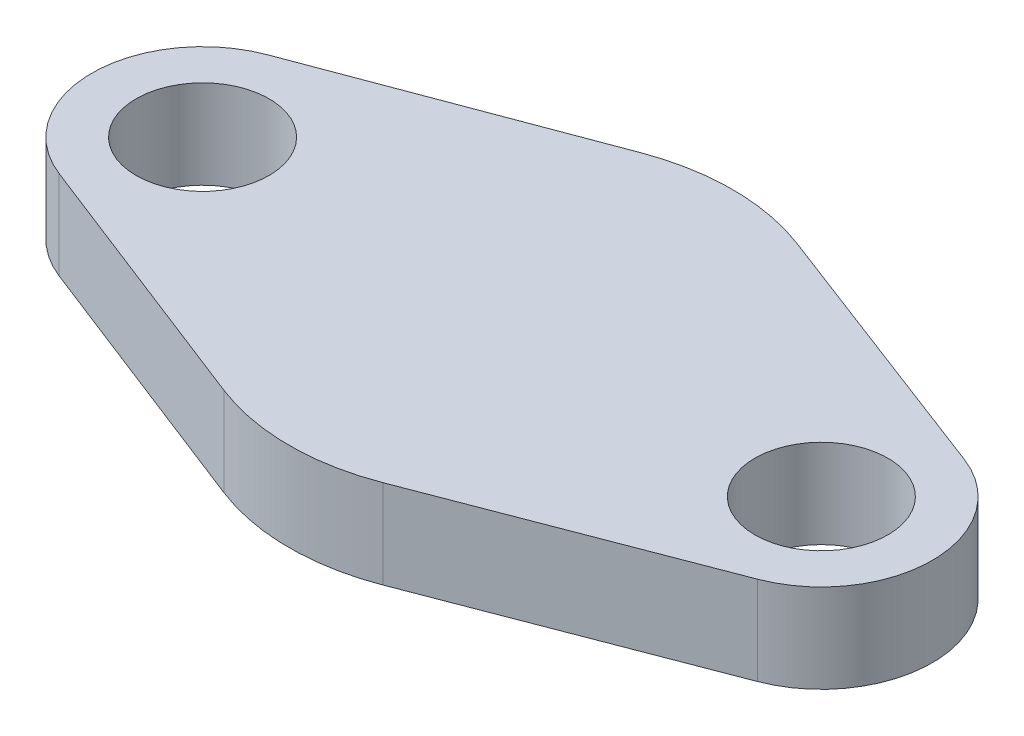
SolidWorks part; units mm, degrees
ref_plane "Plane1" through (0, 0, 0) normal (0, 0, 1) x (1, 0, 0)
ref_plane "Plane2" through (0, 0, 0) normal (0, 1, 0) x (1, 0, 0)
ref_plane "Plane3" through (0, 0, 0) normal (1, 0, 0) x (0, 0, -1)
sketch "Эскиз1" plane through (0, 0, 0) normal (0, -1, 0) x (-1, 0, 0)
  line L0 (-78.9175, 23.3886) -> (-17.835, 46.7109)
  line L1 (17.5567, 46.8163) -> (78.7769, 23.858)
  line L2 (79.077, -22.8436) -> (18.1569, -46.5868)
  line L3 (-17.8793, -46.694) -> (-78.9396, -23.3139)
  arc A0 (-17.8793, -46.694) -> (18.1569, -46.5868) centre (0, 0) ccw
  arc A1 (79.077, -22.8436) -> (78.7769, 23.858) centre (69.9986, 0.4498) ccw
  arc A2 (-78.9175, 23.3886) -> (-78.9396, -23.3139) centre (-70, 0.0331) ccw
  arc A3 (17.5567, 46.8163) -> (-17.835, 46.7109) centre (0, 0) ccw
  dimension "D1" = 100
  dimension "D2" = 50
  dimension "D3" = 50
  dimension "D4" = 70
  dimension "D5" = 70
extrude "Основание-Вытянуть" add sketch "Эскиз1" along normal blind 20
sketch "Sketch1" plane through (0, 0, 0) normal (0, 1, 0) x (1, 0, 0)
  circle A0 centre (-69.9986, 0.4498) radius 15
  arc A1 (-78.7769, 23.858) -> (-79.077, -22.8436) centre (-69.9986, 0.4498) ccw construction
  circle A2 centre (70, 0.0331) radius 15
  arc A3 (78.9396, -23.3139) -> (78.9175, 23.3886) centre (70, 0.0331) ccw construction
  dimension "D1" = 30
extrude "Cut-Extrude1" cut sketch "Sketch1" against normal through all
